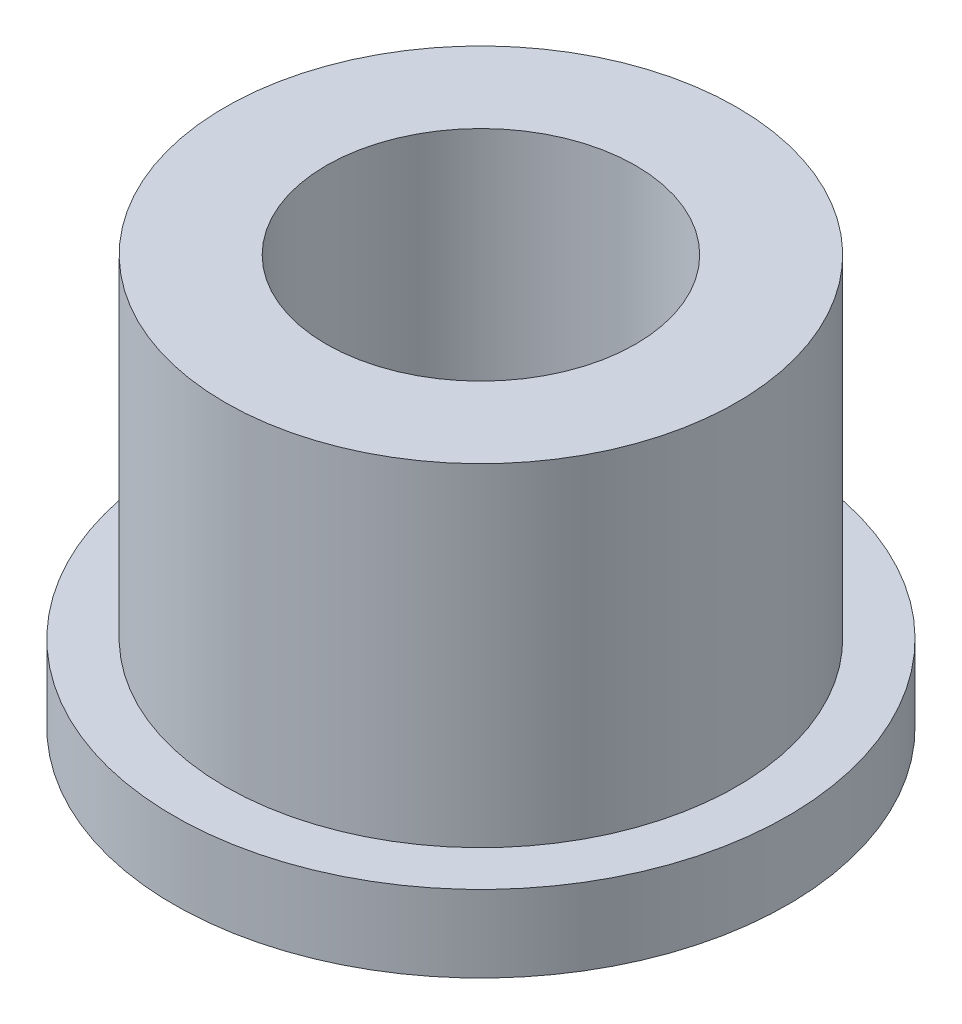
SolidWorks part; units mm, degrees
material "Nylon 101"
ref_plane "Front" through (0, 0, 0) normal (0, 0, 1) x (1, 0, 0)
ref_plane "Top" through (0, 0, 0) normal (0, 1, 0) x (1, 0, 0)
ref_plane "Right" through (0, 0, 0) normal (1, 0, 0) x (0, 0, -1)
sketch "Sketch1" plane through (0, 0, 0) normal (0, 1, 0) x (1, 0, 0)
  circle A0 centre (0, 0) radius 2.4003
  circle A1 centre (0, 0) radius 3.9688
  circle A2 centre (0, 0) radius 4.7625
  dimension "ID" = 4.8006
  dimension "OD" = 7.9375
  dimension "FlangeOD" = 9.525
sketch "Sketch2" plane through (0, 0, 0) normal (0, 1, 0) x (1, 0, 0)
  circle A0 centre (0, 0) radius 2.4003 construction
  circle A1 centre (0, 0) radius 3.9688 construction
  circle A2 centre (0, 0) radius 2.4003
  circle A3 centre (0, 0) radius 3.9688
extrude "Boss-Extrude1" add sketch "Sketch2" along normal blind 6.35
sketch "Sketch3" plane through (0, 0, 0) normal (0, 1, 0) x (1, 0, 0)
  circle A0 centre (0, 0) radius 4.7625 construction
  circle A1 centre (0, 0) radius 3.9688 construction
  circle A2 centre (0, 0) radius 4.7625
  circle A3 centre (0, 0) radius 3.9688
extrude "Boss-Extrude2" add sketch "Sketch3" along normal blind 1.1906
